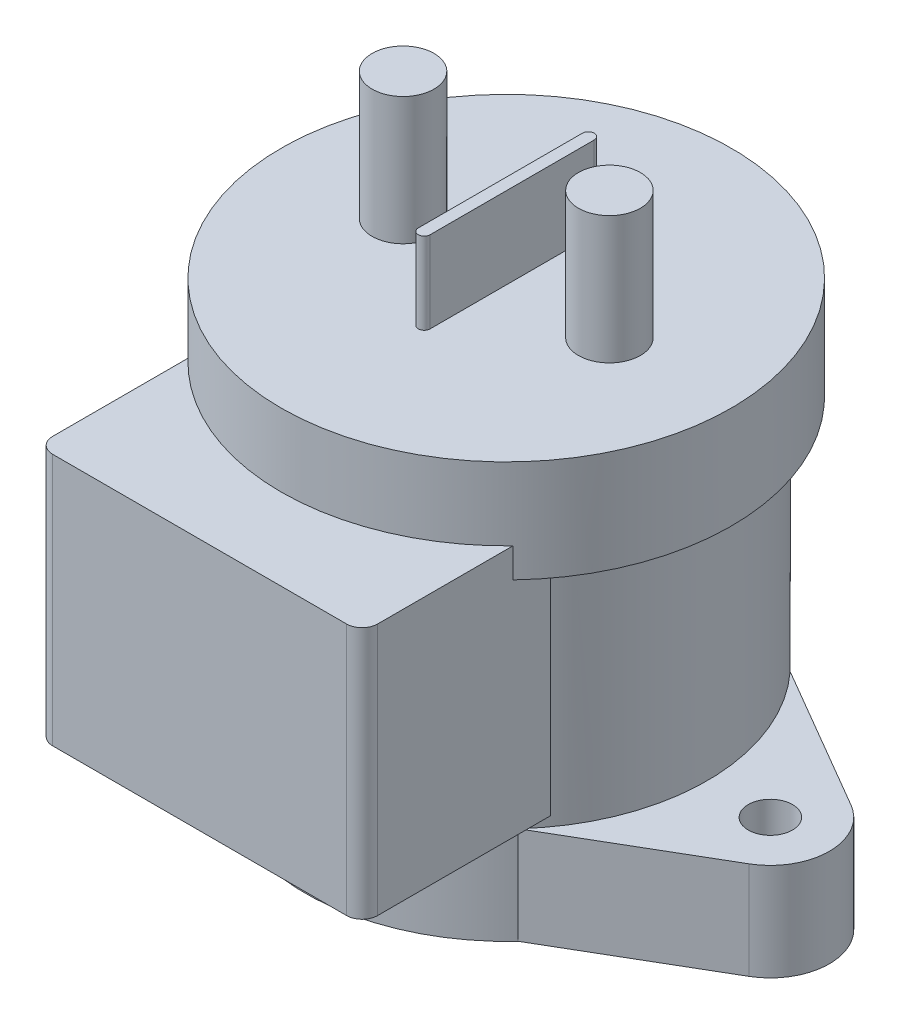
SolidWorks part; units mm, degrees
ref_plane "Front Plane" through (0, 0, 0) normal (0, 0, 1) x (1, 0, 0)
ref_plane "Top Plane" through (0, 0, 0) normal (0, 1, 0) x (1, 0, 0)
ref_plane "Right Plane" through (0, 0, 0) normal (1, 0, 0) x (0, 0, -1)
sketch "Sketch1" plane through (0, 0, 0) normal (0, 1, 0) x (1, 0, 0)
  circle A0 centre (0, 0) radius 29.095
  dimension "D1" = 58.19
extrude "Boss-Extrude1" add sketch "Sketch1" against normal blind 13.208
sketch "Sketch2" plane through (0, -13.208, 0) normal (0, -1, 0) x (1, 0, 0)
  circle A0 centre (0, 0) radius 25.97
  dimension "D1" = 51.94
extrude "Boss-Extrude2" add sketch "Sketch2" along normal blind 42.672
sketch "Sketch3" plane through (0, -55.88, 0) normal (0, -1, 0) x (1, 0, 0)
  line L0 (0, 37.7862) -> (0, -38.9462) construction
  line L1 (37.979, -6.5823) -> (19.1063, -17.5895)
  line L2 (0, 0) -> (69.9091, 0) construction
  line L3 (37.979, 6.5823) -> (19.1063, 17.5895)
  line L4 (-37.979, 6.5823) -> (-19.1063, 17.5895)
  line L5 (-37.979, -6.5823) -> (-19.1063, -17.5895)
  circle A0 centre (34.14, 0) radius 2.86
  arc A1 (19.1063, 17.5895) -> (19.1063, -17.5895) centre (0, 0) cw
  arc A2 (37.979, -6.5823) -> (37.979, 6.5823) centre (34.14, 0) ccw
  arc A3 (-37.979, -6.5823) -> (-37.979, 6.5823) centre (-34.14, 0) cw
  circle A4 centre (-34.14, 0) radius 2.86
  arc A5 (-19.1063, 17.5895) -> (-19.1063, -17.5895) centre (0, 0) ccw
  circle A6 centre (0, 0) radius 25.97 construction
  point P14 (49.2648, 0)
  point P22 (-49.2648, 0)
  dimension "D1" = 5.72
  dimension "D2" = 7.62
  dimension "D3" = 68.28
  dimension "D4" = 35.179
extrude "Boss-Extrude3" add sketch "Sketch3" against normal blind 12.6
sketch "Sketch4" plane through (0, 0, 0) normal (0, 1, 0) x (1, 0, 0)
  line L0 (0, -8.7823) -> (0, 13.0787) construction
  circle A0 centre (13.335, 0) radius 4
  circle A1 centre (-13.335, 0) radius 4
  dimension "D1" = 8
  dimension "D2" = 26.67
extrude "Boss-Extrude4" add sketch "Sketch4" along normal blind 16.49
cosmetic thread "Cosmetic Thread1" parameters "D2"=6.619
cosmetic thread "Cosmetic Thread2" parameters "D2"=6.619
sketch "Sketch5" plane through (0, 0, 0) normal (0, 1, 0) x (1, 0, 0)
  line L0 (0, 0) -> (10.5615, 0) construction
  line L2 (-0.762, 10.603) -> (-0.762, -10.603)
  line L4 (0.762, 10.603) -> (0.762, -10.603)
  line L5 (-0.762, 10.603) -> (0.762, -10.603) construction
  line L6 (-0.762, -10.603) -> (0.762, 10.603) construction
  arc A0 (0.762, 10.603) -> (-0.762, 10.603) centre (0, 10.603) ccw
  arc A1 (0.762, -10.603) -> (-0.762, -10.603) centre (0, -10.603) cw
  point P0 (0, 0)
  point P7 (0, 11.365)
  point P11 (0, -11.365)
  dimension "D1" = 22.73
  dimension "D3" = 0.762
  dimension "D2" = 1.524
extrude "Boss-Extrude5" add sketch "Sketch5" along normal blind 10.541
sketch "Sketch6" plane through (0, -55.88, 0) normal (0, -1, 0) x (1, 0, 0)
  line L0 (-19, 39.63) -> (19, 39.63)
  line L1 (21, 37.63) -> (21, 15.2788)
  line L2 (-21, 37.63) -> (-21, 15.2788)
  arc A0 (19.1063, 17.5895) -> (-19.1063, 17.5895) centre (0, 0) ccw construction
  arc A1 (-21, 15.2788) -> (21, 15.2788) centre (0, 0) cw
  arc A2 (19, 39.63) -> (21, 37.63) centre (19, 37.63) cw
  arc A3 (-21, 37.63) -> (-19, 39.63) centre (-19, 37.63) cw
  arc A4 (-19.1063, -17.5895) -> (19.1063, -17.5895) centre (0, 0) ccw construction
  point P2 (0, 39.63)
  point P8 (0, 25.97)
  point P12 (21, 39.63)
  point P15 (-21, 39.63)
  point P16 (0, -25.97)
  dimension "D2" = 2
  dimension "D1" = 42
  dimension "D3" = 65.6
extrude "Boss-Extrude6" add sketch "Sketch6" against normal blind 32.639 from offset 13.843 offset against normal yes
